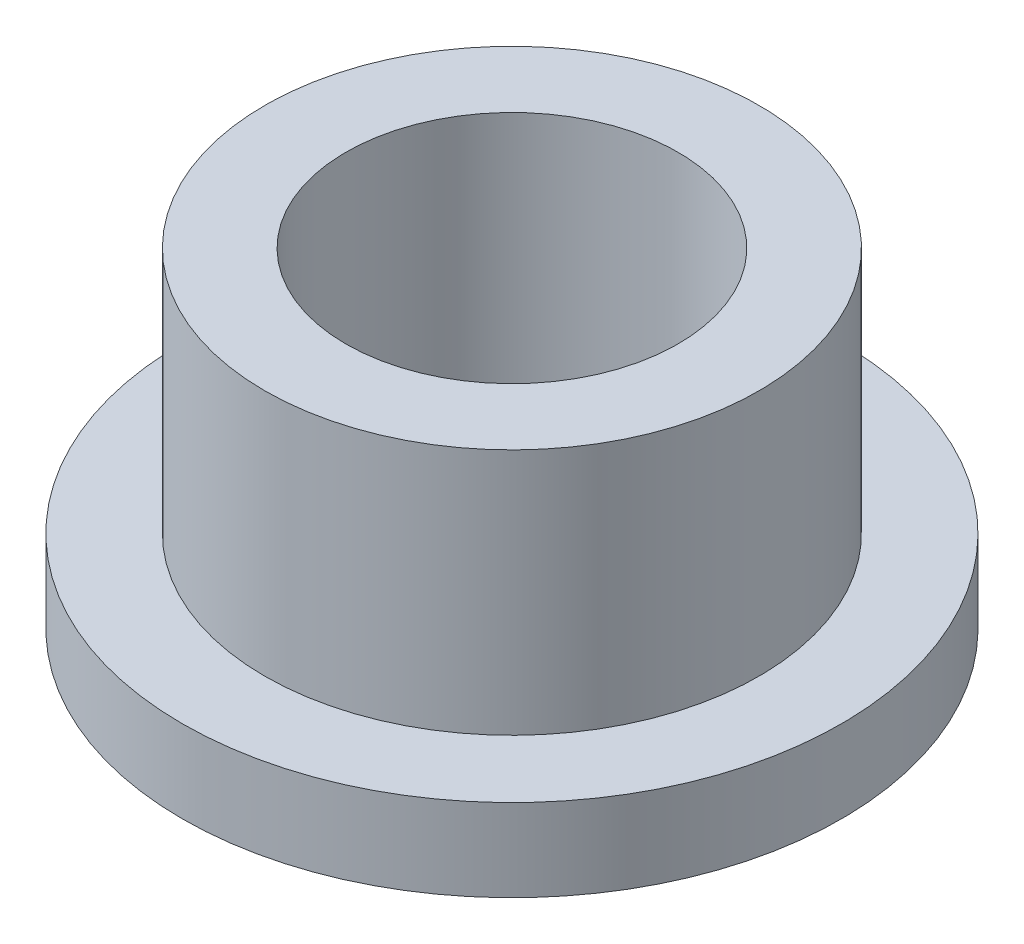
SolidWorks part; units mm, degrees
ref_plane "Front" through (0, 0, 0) normal (0, 0, 1) x (1, 0, 0)
ref_plane "Top" through (0, 0, 0) normal (0, 1, 0) x (1, 0, 0)
ref_plane "Right" through (0, 0, 0) normal (1, 0, 0) x (0, 0, -1)
sketch "Sketch1" plane through (0, 0, 0) normal (0, 1, 0) x (1, 0, 0)
  circle A0 centre (0, 0) radius 3.2004
  circle A1 centre (0, 0) radius 4.7625
  circle A2 centre (0, 0) radius 6.35
  dimension "ID" = 6.4008
  dimension "OD" = 9.525
  dimension "FlangeOD" = 12.7
sketch "Sketch2" plane through (0, 0, 0) normal (0, 1, 0) x (1, 0, 0)
  circle A0 centre (0, 0) radius 3.2004 construction
  circle A1 centre (0, 0) radius 4.7625 construction
  circle A2 centre (0, 0) radius 3.2004
  circle A3 centre (0, 0) radius 4.7625
extrude "Boss-Extrude1" add sketch "Sketch2" along normal blind 6.35
sketch "Sketch3" plane through (0, 0, 0) normal (0, 1, 0) x (1, 0, 0)
  circle A0 centre (0, 0) radius 6.35 construction
  circle A1 centre (0, 0) radius 4.7625 construction
  circle A2 centre (0, 0) radius 6.35
  circle A3 centre (0, 0) radius 4.7625
extrude "Boss-Extrude2" add sketch "Sketch3" along normal blind 1.5875
